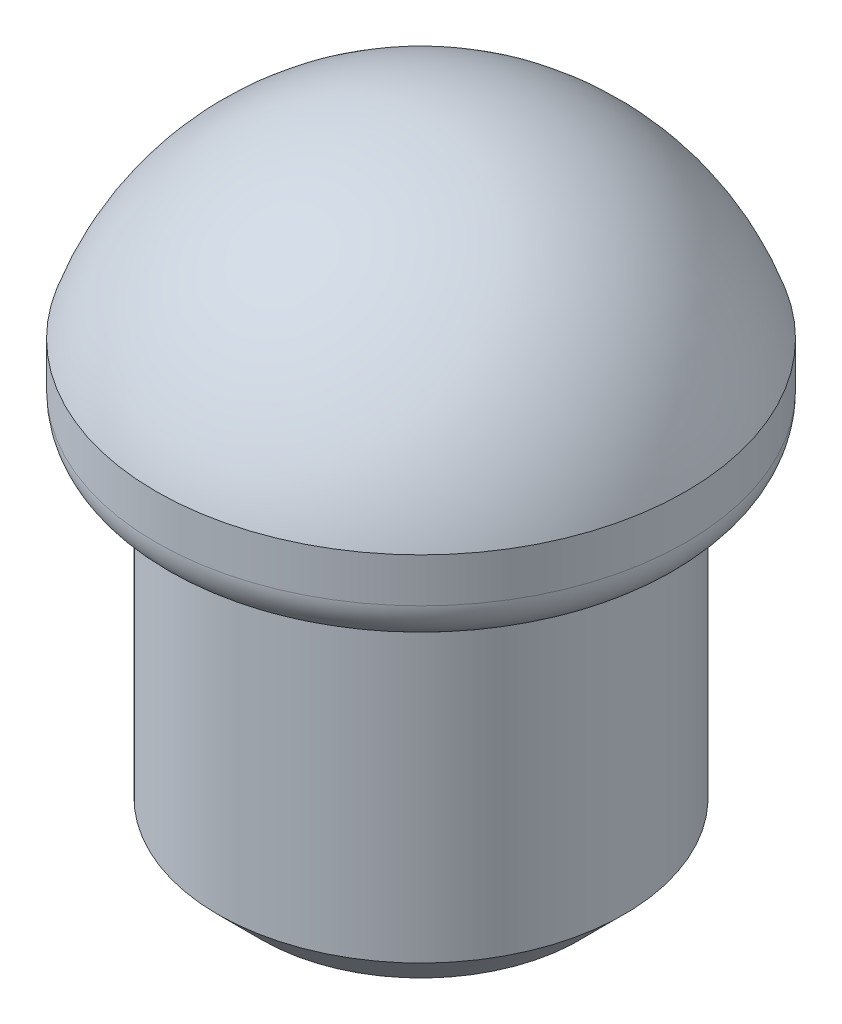
SolidWorks part; units mm, degrees
ref_plane "Front Plane" through (0, 0, 0) normal (0, 0, 1) x (1, 0, 0)
ref_plane "Top Plane" through (0, 0, 0) normal (0, 1, 0) x (1, 0, 0)
ref_plane "Right Plane" through (0, 0, 0) normal (1, 0, 0) x (0, 0, -1)
sketch "Sketch1" plane through (0, 0, 0) normal (0, 1, 0) x (1, 0, 0)
  circle A0 centre (0, 0) radius 2.3
  dimension "D1" = 4.6
extrude "Boss-Extrude1" add sketch "Sketch1" along normal blind 4
sketch "Sketch2" plane through (0, 0, 0) normal (0, 0, 1) x (1, 0, 0)
  line L0 (0, -2.0405) -> (0, 1.0153) construction
  line L1 (2.3, 4) -> (-2.3, 4) construction
  line L3 (-3, 5) -> (-3, 4)
  line L4 (-3, 4) -> (0, 4)
  line L7 (-3, 4) -> (0, 4) construction
  line L8 (0, 7.1623) -> (0, 4)
  arc A0 (0, 7.1623) -> (-3, 5) centre (0, 4) ccw
  point P7 (0, 4)
  dimension "D1" = 1
  dimension "D2" = 6
revolve "Revolve1" add sketch "Sketch2" angle 360 about L0
fillet "Fillet1" radius 0.5 1 edges at (0, 4, -3)
chamfer "Chamfer1" distance 0.5 angle 45 1 edges at (0, 0, 2.3)
